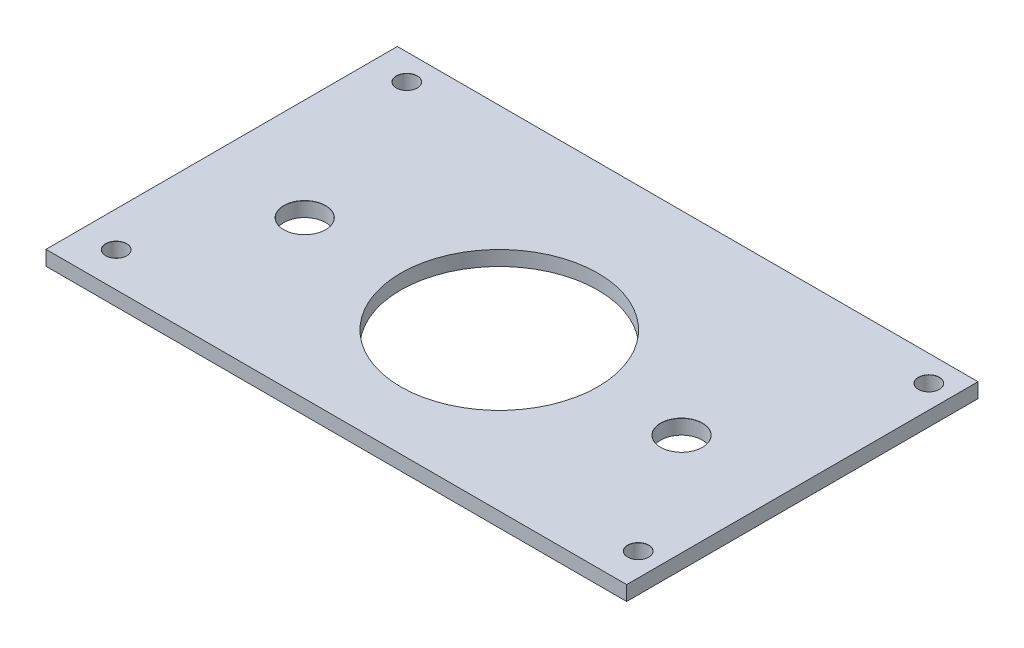
SolidWorks part; units mm, degrees
material "Alloy Steel (SS)"
ref_plane "X-Y Datum" through (0, 0, 0) normal (0, 0, 1) x (1, 0, 0)
ref_plane "X-Z Datum" through (0, 0, 0) normal (0, 1, 0) x (1, 0, 0)
ref_plane "Y-Z Datum" through (0, 0, 0) normal (1, 0, 0) x (0, 0, -1)
sketch "Sketch1" plane through (0, 0, 0) normal (0, 1, 0) x (1, 0, 0)
  line L0 (-64, 0) -> (-42, 0) construction
  line L7 (61.35, 0) -> (39.35, 0) construction
  line L12 (-64, 0) -> (-64, 34)
  line L13 (-64, 34) -> (61.35, 34)
  line L14 (61.35, 34) -> (61.35, 0)
  line L15 (61.35, 0) -> (61.35, -31.35)
  line L16 (61.35, -31.35) -> (-64, -31.35)
  line L17 (-64, -31.35) -> (-64, 0)
  circle A0 centre (0, 0) radius 21.275
  dimension "D1" = 42.55
  dimension "D2" = 34
  dimension "D3" = 31.35
  dimension "D4" = 42
  dimension "D5" = 64
  dimension "D6" = 61.35
extrude "Boss-Extrude1" add sketch "Sketch1" along normal blind 3.175
hole_wizard "M8 Clearance Hole1" positions "Sketch3" profile "Sketch4" hole size "M8" standard "ANSI Metric" end condition through all
sketch "Sketch3" plane through (0, 3.175, 0) normal (0, 1, 0) x (1, 0, 0)
  point P0 (-42, 0)
  point P3 (39.35, 0)
sketch "Sketch4" plane through (-42, 3.175, 0) normal (1, 0, 0) x (0, 0, 1)
  line L0 (0, 0) -> (0, 3.175)
  line L1 (0, 3.175) -> (4.5, 3.175)
  line L2 (4.5, 3.175) -> (4.5, 0.025)
  line L3 (4.5, 0.025) -> (4.525, 0)
  line L5 (4.525, 0) -> (0, 0)
  line L6 (-4.5, 0.025) -> (-4.525, 0) construction
  line L11 (0, -6.35) -> (0, 107.95) construction
  dimension "Thru Hole Dia." = 9
  dimension "Thru Hole Depth" = 3.175
  dimension "Near C'Sink Dia." = 9.05
  dimension "Near C'Sink Angle" = 90
sketch "Sketch9" plane through (0, 3.175, 0) normal (0, 1, 0) x (1, 0, 0)
  line L1 (-64, 34) -> (61.35, 34)
  line L2 (-64, 34) -> (-64, 42)
  line L3 (-64, 42) -> (61.35, 42)
  line L4 (61.35, 34) -> (61.35, 42)
  line L5 (-64, -31.35) -> (61.35, -31.35)
  line L6 (-64, -31.35) -> (-64, -33.85)
  line L7 (-64, -33.85) -> (61.35, -33.85)
  line L8 (61.35, -31.35) -> (61.35, -33.85)
  dimension "D1" = 8
  dimension "D2" = 2.5
extrude "Boss-Extrude2" add sketch "Sketch9" along direction (0, -1, 0) on the side against the normal up to surface (3.175 mm away)
hole_wizard "M4 Clearance Hole1" positions "Sketch7" profile "Sketch8" hole size "M4" standard "ANSI Metric" end condition through all
sketch "Sketch7" plane through (0, 3.175, 0) normal (0, 1, 0) x (1, 0, 0)
  line L0 (0, 0) -> (-56.35, 0) construction
  line L3 (-56.35, 36.388) -> (-56.35, 0) construction
  line L5 (-56.35, 0) -> (-56.35, -26.35) construction
  line L6 (0, 0) -> (0, 12.1798) construction
  line L7 (0, 0) -> (56.35, 0) construction
  circle A0 centre (-56.35, 36.388) radius 6.75
  circle A1 centre (-56.35, -26.35) radius 6.75
  circle A4 centre (56.35, 36.388) radius 6.75
  circle A5 centre (56.35, -26.35) radius 6.75
  point P1 (-56.35, 36.388)
  point P3 (-56.35, -26.35)
  point P37 (56.35, -26.35)
  point P43 (56.35, 36.388)
  dimension "D3" = 13.5
  dimension "D1" = 56.35
  dimension "D2" = 26.35
  dimension "D4" = 36.388
sketch "Sketch8" plane through (-56.35, 3.175, -36.388) normal (1, 0, 0) x (0, 0, 1)
  line L0 (0, 0) -> (0, 3.175)
  line L1 (0, 3.175) -> (2.25, 3.175)
  line L2 (2.25, 3.175) -> (2.25, 0.025)
  line L3 (2.25, 0.025) -> (2.275, 0)
  line L5 (2.275, 0) -> (0, 0)
  line L6 (-2.25, 0.025) -> (-2.275, 0) construction
  line L11 (0, -6.35) -> (0, 107.95) construction
  dimension "Thru Hole Dia." = 4.5
  dimension "Thru Hole Depth" = 3.175
  dimension "Near C'Sink Dia." = 4.55
  dimension "Near C'Sink Angle" = 90
